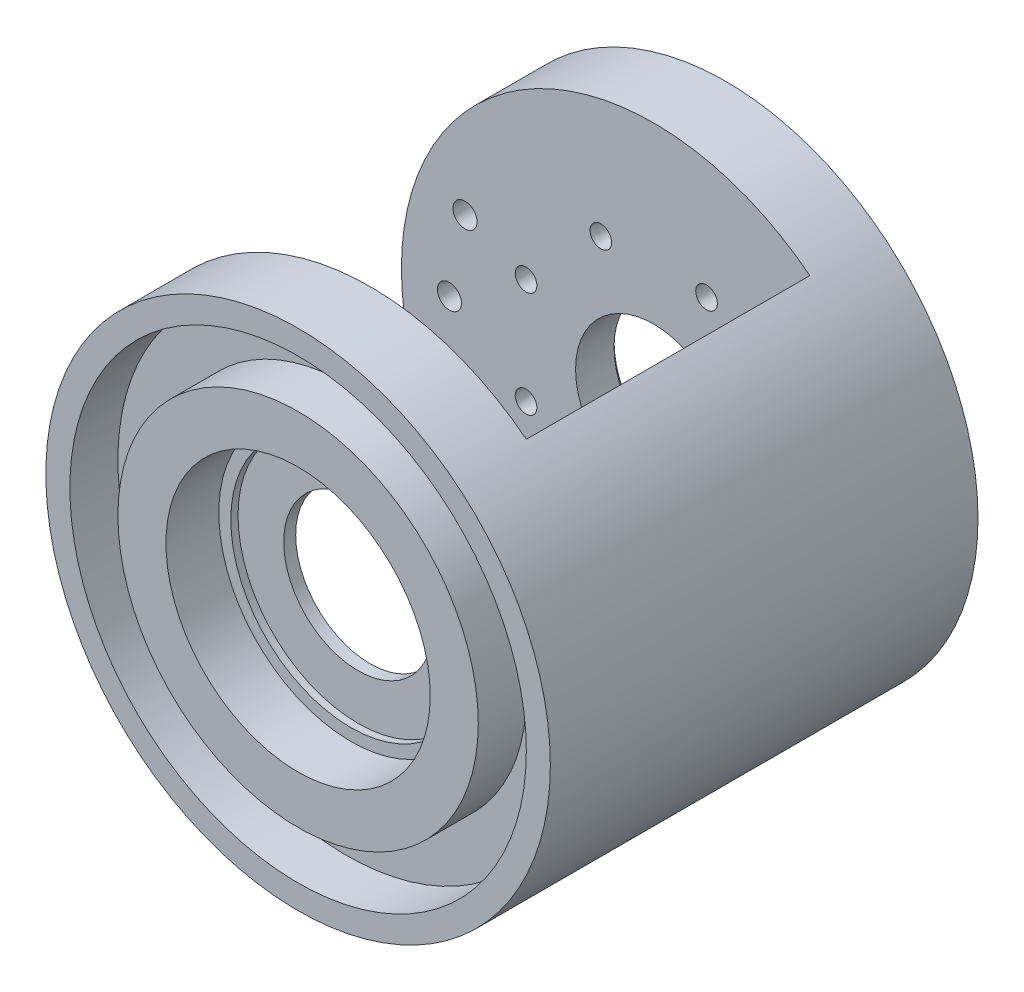
SolidWorks part; units mm, degrees
ref_plane "前视基准面" through (0, 0, 0) normal (0, 0, 1) x (1, 0, 0)
ref_plane "上视基准面" through (0, 0, 0) normal (0, 1, 0) x (1, 0, 0)
ref_plane "右视基准面" through (0, 0, 0) normal (1, 0, 0) x (0, 0, -1)
sketch "草图1" plane through (0, 0, 0) normal (0, 0, 1) x (1, 0, 0)
  circle A0 centre (0, 0) radius 105
  dimension "D1" = 210
extrude "拉伸1" add sketch "草图1" along normal blind 178
sketch "草图2" plane through (0, 0, 178) normal (0, 0, 1) x (1, 0, 0)
  circle A0 centre (0, 0) radius 95
  circle A1 centre (0, 0) radius 75
extrude "切除-拉伸1" cut sketch "草图2" against normal blind 20
sketch "草图3" plane through (0, 0, 178) normal (0, 0, 1) x (1, 0, 0)
  circle A0 centre (0, 0) radius 55
extrude "切除-拉伸2" cut sketch "草图3" against normal blind 22
sketch "草图4" plane through (0, 0, 156) normal (0, 0, 1) x (1, 0, 0)
  circle A0 centre (0, 0) radius 50
  dimension "D1" = 100
extrude "切除-拉伸3" cut sketch "草图4" against normal blind 3
sketch "草图5" plane through (0, 0, 153) normal (0, 0, 1) x (1, 0, 0)
  circle A0 centre (0, 0) radius 31
  dimension "D1" = 62
extrude "切除-拉伸4" cut sketch "草图5" against normal blind 23
sketch "草图6" plane through (0, 0, 0) normal (0, 0, -1) x (-1, 0, 0)
  circle A0 centre (0, 0) radius 95
  circle A1 centre (0, 0) radius 75
  dimension "D1" = 190
  dimension "D2" = 150
extrude "切除-拉伸5" cut sketch "草图6" against normal blind 20
sketch "草图7" plane through (0, 0, 0) normal (0, 0, -1) x (-1, 0, 0)
  circle A0 centre (0, 0) radius 67.5
extrude "切除-拉伸6" cut sketch "草图7" against normal blind 12
sketch "草图8" plane through (0, 0, 12) normal (0, 0, -1) x (-1, 0, 0)
  circle A0 centre (0, 0) radius 32.5
  dimension "D1" = 65
extrude "切除-拉伸7" cut sketch "草图8" against normal blind 20
sketch "草图9" plane through (0, 0, 12) normal (0, 0, -1) x (-1, 0, 0)
  circle A1 centre (53.1231, 22.0043) radius 4.5
  circle A2 centre (53.1231, -22.0043) radius 4.5
  circle A3 centre (22.0043, -53.1231) radius 4.5
  circle A4 centre (-22.0043, -53.1231) radius 4.5
  circle A5 centre (-53.1231, -22.0043) radius 4.5
  circle A6 centre (-53.1231, 22.0043) radius 4.5
  circle A7 centre (-22.0043, 53.1231) radius 4.5
  circle A10 centre (22.0043, 53.1231) radius 4.5
extrude "切除-拉伸8" cut sketch "草图9" against normal blind 30
ref_plane "基准面1" through (0, 0, 30) normal (0, 0, -1) x (-1, 0, 0)
sketch "草图10" plane through (0, 0, 30) normal (0, 0, -1) x (-1, 0, 0)
  line L2 (-65, 0) -> (-65, 82.4621)
  line L3 (-65, 0) -> (-65, -82.4621)
  arc A0 (-65, -82.4621) -> (-65, 82.4621) centre (0, 0) ccw
extrude "切除-拉伸9" cut sketch "草图10" against normal blind 118
sketch "草图11" plane through (0, 0, 0) normal (0, 0, -1) x (-1, 0, 0)
  circle A1 centre (78.5298, 32.5281) radius 5
  circle A2 centre (85, 0) radius 5
  circle A3 centre (78.5298, -32.5281) radius 5
extrude "切除-拉伸10" cut sketch "草图11" against normal blind 50
chamfer "倒角1" distance 2 angle 45 1 edges at (-32.5, 0, 12)
